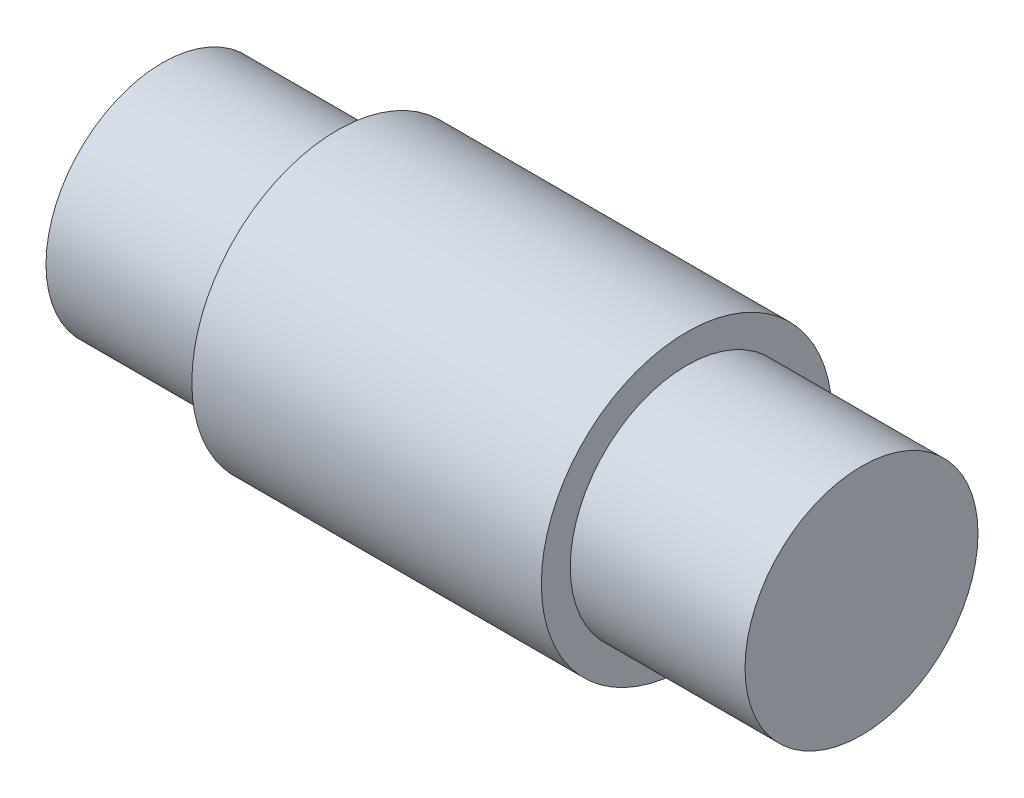
SolidWorks part; units mm, degrees
ref_plane "Front Plane" through (0, 0, 0) normal (0, 0, 1) x (1, 0, 0)
ref_plane "Top Plane" through (0, 0, 0) normal (0, 1, 0) x (1, 0, 0)
ref_plane "Right Plane" through (0, 0, 0) normal (1, 0, 0) x (0, 0, -1)
sketch "Sketch1" plane through (0, 0, 0) normal (0, 0, 1) x (1, 0, 0)
  line L0 (0, 0) -> (19.05, 0)
  line L1 (19.05, 0) -> (19.05, 3.175)
  line L2 (19.05, 3.175) -> (14.2875, 3.175)
  line L3 (14.2875, 3.175) -> (14.2875, 3.9624)
  line L4 (14.2875, 3.9624) -> (4.7625, 3.9624)
  line L5 (4.7625, 3.9624) -> (4.7625, 3.175)
  line L6 (4.7625, 3.175) -> (0, 3.175)
  line L7 (0, 3.175) -> (0, 0)
  point P3 (4.6992, 3.9624)
  dimension "D1" = 19.05
  dimension "D2" = 3.9624
  dimension "D3" = 3.175
  dimension "D4" = 9.525
revolve "Revolve1" add sketch "Sketch1" angle 360 about L0
